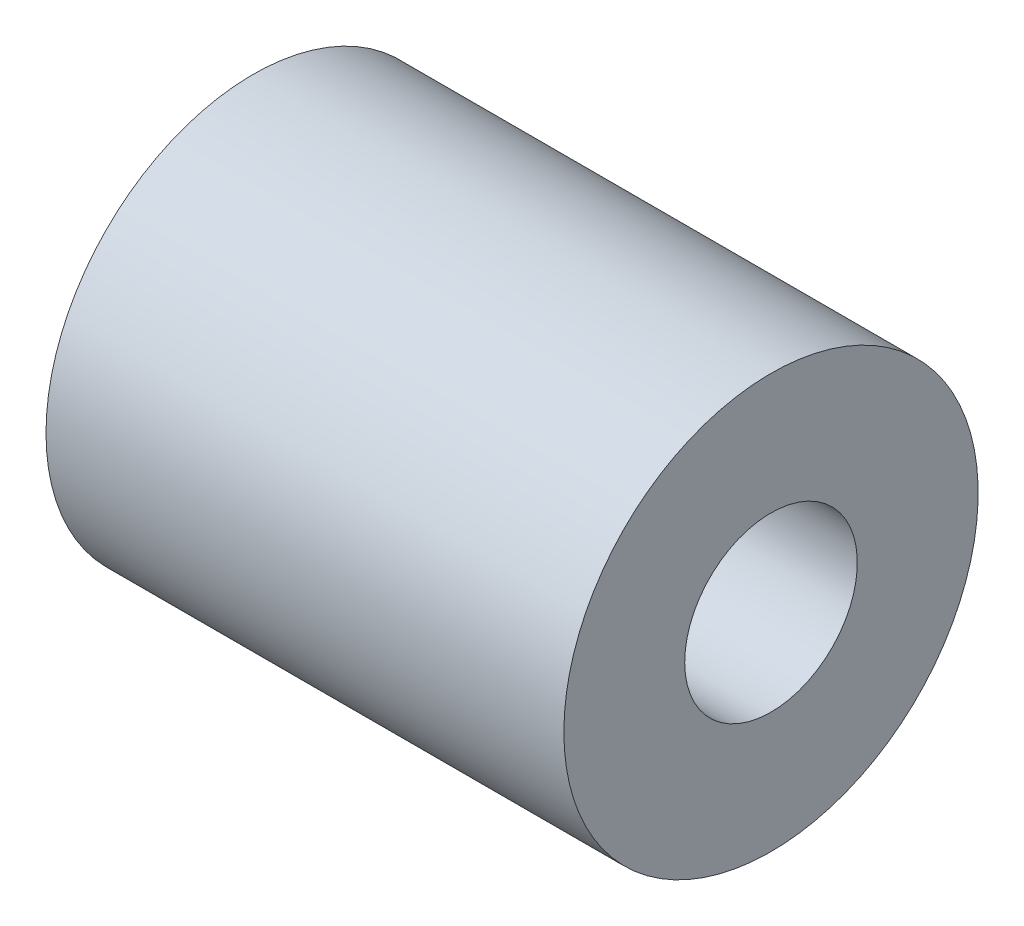
SolidWorks part; units mm, degrees
ref_plane "前视基准面" through (0, 0, 0) normal (0, 0, 1) x (1, 0, 0)
ref_plane "上视基准面" through (0, 0, 0) normal (0, 1, 0) x (1, 0, 0)
ref_plane "右视基准面" through (0, 0, 0) normal (1, 0, 0) x (0, 0, -1)
sketch "草图1" plane through (0, 0, 0) normal (0, 0, 1) x (1, 0, 0)
  line L0 (0, 17.7558) -> (0, -13.6395) construction
  line L1 (-25.0116, 0) -> (18.593, 0) construction
  line L2 (0, 1.5) -> (0, 3.6)
  line L3 (0, 3.6) -> (-9, 3.6)
  line L4 (-9, 3.6) -> (-9, 1.5)
  line L5 (-9, 1.5) -> (0, 1.5)
  dimension "D1" = 3
  dimension "D2" = 7.2
  dimension "D3" = 9
revolve "旋转1" add sketch "草图1" angle 360 about L1
